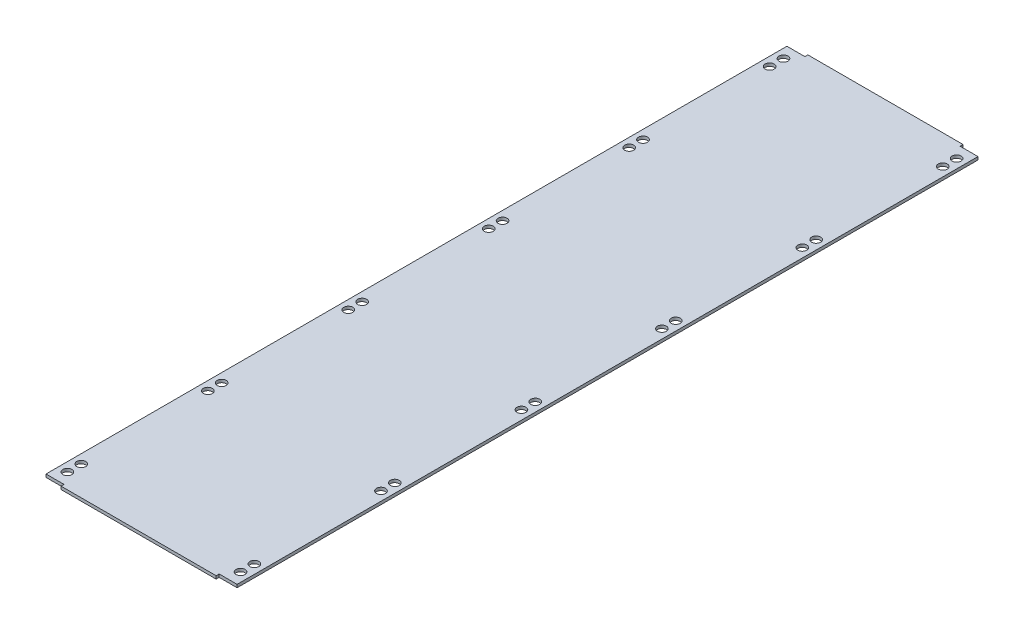
SolidWorks part; units mm, degrees
ref_plane "Front Plane" through (0, 0, 0) normal (0, 0, 1) x (1, 0, 0)
ref_plane "Top Plane" through (0, 0, 0) normal (0, 1, 0) x (1, 0, 0)
ref_plane "Right Plane" through (0, 0, 0) normal (1, 0, 0) x (0, 0, -1)
sketch "Sketch1" plane through (0, 0, 0) normal (0, 1, 0) x (1, 0, 0)
  line L1 (0, 0) -> (83, 0)
  line L2 (0, 0) -> (0, 327)
  line L3 (0, 327) -> (83, 327)
  line L4 (83, 0) -> (83, 327)
  dimension "D1" = 83
  dimension "D2" = 327
extrude "Boss-Extrude1" add sketch "Sketch1" along normal blind 1.3
sketch "Sketch2" plane through (0, 1.3, 0) normal (0, 1, 0) x (1, 0, 0)
  line L0 (0, 327) -> (0, 0) construction
  line L1 (83, 327) -> (0, 327) construction
  circle A0 centre (3.9, 319) radius 1.95
  circle A1 centre (3.9, 313) radius 1.95
  circle A2 centre (79.1, 319) radius 1.95
  circle A3 centre (79.1, 313) radius 1.95
  circle A4 centre (79.1, 258) radius 1.95
  circle A5 centre (79.1, 252) radius 1.95
  circle A6 centre (79.1, 197) radius 1.95
  circle A7 centre (79.1, 191) radius 1.95
  circle A8 centre (79.1, 136) radius 1.95
  circle A9 centre (79.1, 130) radius 1.95
  circle A10 centre (79.1, 75) radius 1.95
  circle A11 centre (79.1, 69) radius 1.95
  circle A12 centre (79.1, 14) radius 1.95
  circle A13 centre (79.1, 8) radius 1.95
  circle A14 centre (3.9, 258) radius 1.95
  circle A15 centre (3.9, 252) radius 1.95
  circle A16 centre (3.9, 197) radius 1.95
  circle A17 centre (3.9, 191) radius 1.95
  circle A18 centre (3.9, 136) radius 1.95
  circle A19 centre (3.9, 130) radius 1.95
  circle A20 centre (3.9, 75) radius 1.95
  circle A21 centre (3.9, 69) radius 1.95
  circle A22 centre (3.9, 14) radius 1.95
  circle A23 centre (3.9, 8) radius 1.95
  dimension "D1" = 3.9
  dimension "D2" = 3.9
  dimension "D3" = 3.9
  dimension "D4" = 3.9
  dimension "D5" = 6
  dimension "D6" = 8
  dimension "D7" = 2
  dimension "D8" = 6
extrude "Cut-Extrude1" cut sketch "Sketch2" against normal blind 10
sketch "Sketch4" plane through (0, 1.3, 0) normal (0, 1, 0) x (1, 0, 0)
  line L0 (83, 0) -> (83, 327) construction
  line L1 (0, 327) -> (83, 327)
  line L2 (0, 327) -> (0, 324.4)
  line L3 (0, 324.4) -> (83, 324.4)
  line L4 (83, 327) -> (83, 324.4)
  line L6 (0, 0) -> (83, 0)
  line L7 (0, 0) -> (0, 2.6)
  line L8 (0, 2.6) -> (83, 2.6)
  line L9 (83, 0) -> (83, 2.6)
  dimension "D1" = 2.6
  dimension "D2" = 2.6
extrude "Cut-Extrude2" cut sketch "Sketch4" against normal blind 10
sketch "Sketch5" plane through (0, 1.3, 0) normal (0, 1, 0) x (1, 0, 0)
  line L0 (0, 324.4) -> (83, 324.4) construction
  line L1 (7.8, 324.4) -> (75.2, 324.4)
  line L2 (7.8, 324.4) -> (7.8, 325.7)
  line L3 (7.8, 325.7) -> (75.2, 325.7)
  line L4 (75.2, 324.4) -> (75.2, 325.7)
  line L5 (0, 324.4) -> (0, 2.6) construction
  line L6 (83, 2.6) -> (0, 2.6) construction
  line L7 (7.8, 2.6) -> (75.2, 2.6)
  line L8 (7.8, 2.6) -> (7.8, 1.3)
  line L9 (7.8, 1.3) -> (75.2, 1.3)
  line L10 (75.2, 2.6) -> (75.2, 1.3)
  dimension "D1" = 67.4
  dimension "D2" = 7.8
  dimension "D3" = 1.3
  dimension "D4" = 1.3
  dimension "D5" = 67.4
  dimension "D6" = 7.8
extrude "Boss-Extrude2" add sketch "Sketch5" against normal blind 1.3
